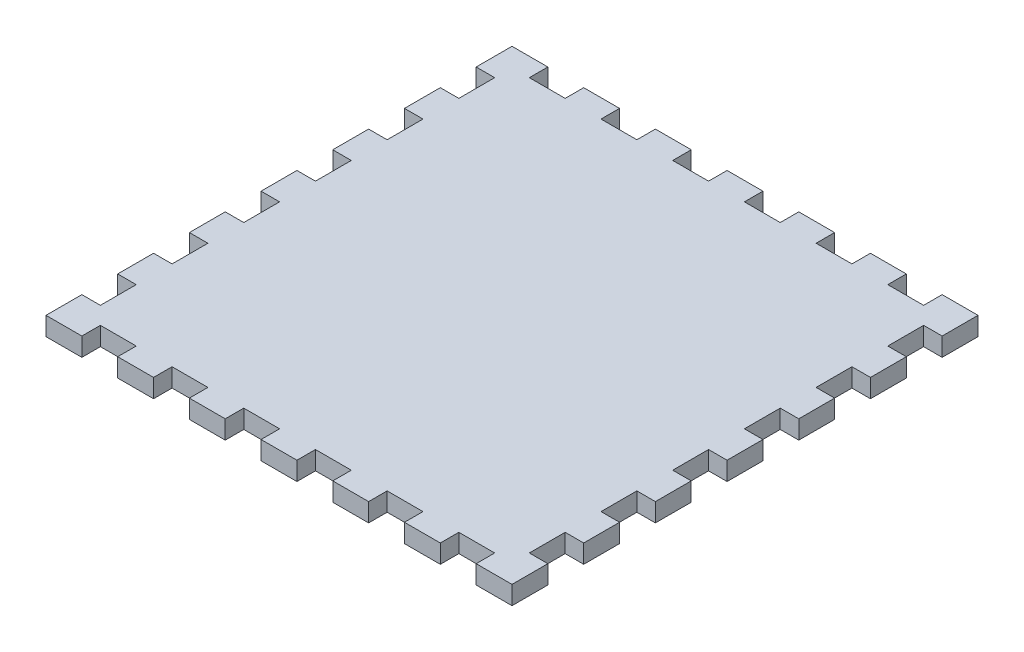
SolidWorks part; units mm, degrees
material "Acrylic (Medium-high impact)"
ref_plane "Front Plane" through (0, 0, 0) normal (0, 0, 1) x (1, 0, 0)
ref_plane "Top Plane" through (0, 0, 0) normal (0, 1, 0) x (1, 0, 0)
ref_plane "Right Plane" through (0, 0, 0) normal (1, 0, 0) x (0, 0, -1)
sketch "Sketch1" plane through (0, 0, 0) normal (0, 1, 0) x (1, 0, 0)
  line L1 (-40, -40) -> (40, -40)
  line L2 (-40, -40) -> (-40, 40)
  line L3 (-40, 40) -> (40, 40)
  line L4 (40, -40) -> (40, 40)
  line L5 (-40, -40) -> (40, 40) construction
  line L6 (-40, 40) -> (40, -40) construction
  point P0 (0, 0)
  dimension "D1" = 80
extrude "Boss-Extrude1" add sketch "Sketch1" along normal mid plane 3.175
sketch "Sketch2" plane through (0, 1.5875, 0) normal (0, 1, 0) x (1, 0, 0)
  line L0 (0, 0) -> (50000, 0) construction
  line L1 (40, -40) -> (40, 40) construction
  line L2 (0, 0) -> (0, -50000) construction
  line L3 (-40, -40) -> (40, -40) construction
  line L4 (-40, 40) -> (-40, 33.8462)
  line L5 (-40, 40) -> (-40, -40) construction
  line L6 (-40, 33.8462) -> (-36.82, 33.8462)
  line L7 (-36.82, 33.8462) -> (-36.82, 27.6923)
  line L8 (-36.82, 27.6923) -> (-40, 27.6923)
  line L9 (-36.82, 15.3846) -> (-40, 15.3846)
  line L10 (-36.82, 21.5385) -> (-36.82, 15.3846)
  line L11 (-40, 21.5385) -> (-36.82, 21.5385)
  line L12 (-40, 27.6923) -> (-40, 21.5385)
  line L13 (-36.82, 3.0769) -> (-40, 3.0769)
  line L14 (-36.82, 9.2308) -> (-36.82, 3.0769)
  line L15 (-40, 9.2308) -> (-36.82, 9.2308)
  line L16 (-40, 15.3846) -> (-40, 9.2308)
  line L17 (-36.82, -9.2308) -> (-40, -9.2308)
  line L18 (-36.82, -3.0769) -> (-36.82, -9.2308)
  line L19 (-40, -3.0769) -> (-36.82, -3.0769)
  line L20 (-40, 3.0769) -> (-40, -3.0769)
  line L21 (-36.82, -21.5385) -> (-40, -21.5385)
  line L22 (-36.82, -15.3846) -> (-36.82, -21.5385)
  line L23 (-40, -15.3846) -> (-36.82, -15.3846)
  line L24 (-40, -9.2308) -> (-40, -15.3846)
  line L25 (-36.82, -33.8462) -> (-40, -33.8462)
  line L26 (-36.82, -27.6923) -> (-36.82, -33.8462)
  line L27 (-40, -27.6923) -> (-36.82, -27.6923)
  line L28 (-40, -21.5385) -> (-40, -27.6923)
  line L29 (-40, -33.8462) -> (-40, -40)
  line L30 (40, -33.8462) -> (40, -40)
  line L31 (40, -21.5385) -> (40, -27.6923)
  line L32 (40, -27.6923) -> (36.82, -27.6923)
  line L33 (36.82, -27.6923) -> (36.82, -33.8462)
  line L34 (36.82, -33.8462) -> (40, -33.8462)
  line L35 (40, -9.2308) -> (40, -15.3846)
  line L36 (40, -15.3846) -> (36.82, -15.3846)
  line L37 (36.82, -15.3846) -> (36.82, -21.5385)
  line L38 (36.82, -21.5385) -> (40, -21.5385)
  line L39 (40, 3.0769) -> (40, -3.0769)
  line L40 (40, -3.0769) -> (36.82, -3.0769)
  line L41 (36.82, -3.0769) -> (36.82, -9.2308)
  line L42 (36.82, -9.2308) -> (40, -9.2308)
  line L43 (40, 15.3846) -> (40, 9.2308)
  line L44 (40, 9.2308) -> (36.82, 9.2308)
  line L45 (36.82, 9.2308) -> (36.82, 3.0769)
  line L46 (36.82, 3.0769) -> (40, 3.0769)
  line L47 (40, 27.6923) -> (40, 21.5385)
  line L48 (40, 21.5385) -> (36.82, 21.5385)
  line L49 (36.82, 21.5385) -> (36.82, 15.3846)
  line L50 (36.82, 15.3846) -> (40, 15.3846)
  line L51 (36.82, 27.6923) -> (40, 27.6923)
  line L52 (36.82, 33.8462) -> (36.82, 27.6923)
  line L53 (40, 33.8462) -> (36.82, 33.8462)
  line L54 (40, 40) -> (40, 33.8462)
  line L55 (-40, 40) -> (-33.8462, 40)
  line L56 (40, 40) -> (-40, 40) construction
  line L57 (-33.8462, 40) -> (-33.8462, 36.82)
  line L58 (-33.8462, 36.82) -> (-27.6923, 36.82)
  line L59 (-27.6923, 36.82) -> (-27.6923, 40)
  line L60 (-27.6923, 40) -> (-21.5385, 40)
  line L61 (-21.5385, 40) -> (-21.5385, 36.82)
  line L62 (-21.5385, 36.82) -> (-15.3846, 36.82)
  line L63 (-15.3846, 36.82) -> (-15.3846, 40)
  line L64 (-15.3846, 40) -> (-9.2308, 40)
  line L65 (-9.2308, 40) -> (-9.2308, 36.82)
  line L66 (-9.2308, 36.82) -> (-3.0769, 36.82)
  line L67 (-3.0769, 36.82) -> (-3.0769, 40)
  line L68 (-3.0769, 40) -> (3.0769, 40)
  line L69 (3.0769, 40) -> (3.0769, 36.82)
  line L70 (3.0769, 36.82) -> (9.2308, 36.82)
  line L71 (9.2308, 36.82) -> (9.2308, 40)
  line L72 (9.2308, 40) -> (15.3846, 40)
  line L73 (15.3846, 40) -> (15.3846, 36.82)
  line L74 (15.3846, 36.82) -> (21.5385, 36.82)
  line L75 (21.5385, 36.82) -> (21.5385, 40)
  line L76 (21.5385, 40) -> (27.6923, 40)
  line L77 (27.6923, 40) -> (27.6923, 36.82)
  line L78 (27.6923, 36.82) -> (33.8462, 36.82)
  line L79 (33.8462, 36.82) -> (33.8462, 40)
  line L80 (33.8462, 40) -> (40, 40)
  line L81 (-40, -40) -> (-33.8462, -40)
  line L82 (33.8462, -40) -> (40, -40)
  line L83 (33.8462, -36.82) -> (33.8462, -40)
  line L84 (27.6923, -36.82) -> (33.8462, -36.82)
  line L85 (27.6923, -40) -> (27.6923, -36.82)
  line L86 (21.5385, -40) -> (27.6923, -40)
  line L87 (21.5385, -36.82) -> (21.5385, -40)
  line L88 (15.3846, -36.82) -> (21.5385, -36.82)
  line L89 (15.3846, -40) -> (15.3846, -36.82)
  line L90 (9.2308, -40) -> (15.3846, -40)
  line L91 (9.2308, -36.82) -> (9.2308, -40)
  line L92 (3.0769, -36.82) -> (9.2308, -36.82)
  line L93 (3.0769, -40) -> (3.0769, -36.82)
  line L94 (-3.0769, -40) -> (3.0769, -40)
  line L95 (-3.0769, -36.82) -> (-3.0769, -40)
  line L96 (-9.2308, -36.82) -> (-3.0769, -36.82)
  line L97 (-9.2308, -40) -> (-9.2308, -36.82)
  line L98 (-15.3846, -40) -> (-9.2308, -40)
  line L99 (-15.3846, -36.82) -> (-15.3846, -40)
  line L100 (-21.5385, -36.82) -> (-15.3846, -36.82)
  line L101 (-21.5385, -40) -> (-21.5385, -36.82)
  line L102 (-27.6923, -40) -> (-21.5385, -40)
  line L103 (-27.6923, -36.82) -> (-27.6923, -40)
  line L104 (-33.8462, -36.82) -> (-27.6923, -36.82)
  line L105 (-33.8462, -40) -> (-33.8462, -36.82)
  point P5 (40, 0)
  point P10 (0, -40)
  dimension "D1" = 3.18
  dimension "D2" = 3.18
  dimension "D3" = 6
  dimension "D6" = 6
extrude "Cut-Extrude1" cut sketch "Sketch2" against normal through all flip side to cut
